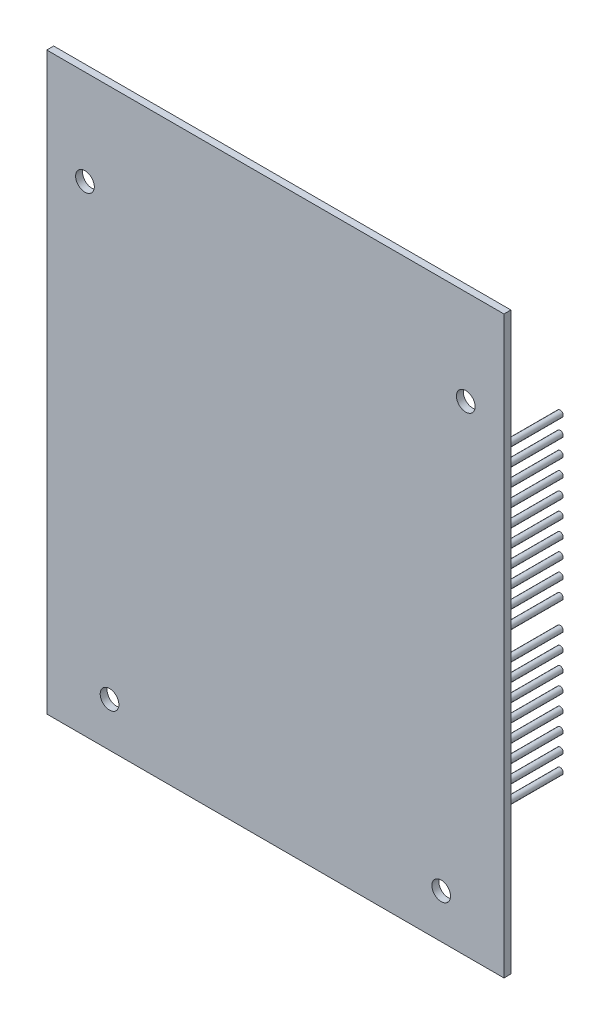
SolidWorks part; units mm, degrees
ref_plane "Alzado" through (0, 0, 0) normal (0, 0, 1) x (1, 0, 0)
ref_plane "Planta" through (0, 0, 0) normal (0, 1, 0) x (1, 0, 0)
ref_plane "Vista lateral" through (0, 0, 0) normal (1, 0, 0) x (0, 0, -1)
sketch "Croquis1" plane through (0, 0, 0) normal (0, 0, 1) x (1, 0, 0)
  line L1 (0, 83.058) -> (66.04, 83.058)
  line L2 (0, 83.058) -> (0, 0)
  line L3 (0, 0) -> (66.04, 0)
  line L4 (66.04, 83.058) -> (66.04, 0)
  dimension "D1" = 66.04
  dimension "D2" = 83.058
extrude "Saliente-Extruir1" add sketch "Croquis1" along normal blind 1
sketch "Croquis7" plane through (0, 0, 1) normal (0, 0, 1) x (1, 0, 0)
  line L0 (0, 6.3729) -> (66.04, 6.3729) construction
  line L1 (0, 83.058) -> (0, 0) construction
  line L2 (66.04, 0) -> (66.04, 83.058) construction
  line L3 (66.04, 69.375) -> (0, 69.375) construction
  line L4 (5.5194, 0) -> (5.5194, 83.058) construction
  line L5 (0, 0) -> (66.04, 0) construction
  line L6 (66.04, 83.058) -> (0, 83.058) construction
  line L7 (9.0678, 0) -> (9.0678, 83.058) construction
  line L8 (56.9722, 0) -> (56.9722, 83.058) construction
  line L9 (60.5206, 0) -> (60.5206, 83.058) construction
  line L10 (33.02, 83.058) -> (33.02, 0) construction
  dimension "D1" = 13.683
  dimension "D2" = 6.3729
  dimension "D3" = 9.0678
  dimension "D4" = 9.0678
  dimension "D5" = 5.5194
  dimension "D6" = 5.5194
  dimension "D7" = 23.9522
  dimension "D8" = 23.9522
  dimension "D9" = 27.5006
  dimension "D10" = 27.5006
hole_wizard "Taladro de margen para M2.51" positions "Croquis3D6" profile "Croquis8" hole size "M2.5" standard "ISO" end condition through all
sketch3d "Croquis3D6"
  line L0 (66.04, 69.375, 1) -> (0, 69.375, 1) construction
  line L1 (5.5194, 0, 1) -> (5.5194, 83.058, 1) construction
  line L2 (60.5206, 0, 1) -> (60.5206, 83.058, 1) construction
  line L3 (0, 6.3729, 1) -> (66.04, 6.3729, 1) construction
  line L4 (9.0678, 0, 1) -> (9.0678, 83.058, 1) construction
  line L5 (56.9722, 0, 1) -> (56.9722, 83.058, 1) construction
  point P0 (5.5194, 69.375, 1)
  point P6 (60.5206, 69.375, 1)
  point P10 (9.0678, 6.3729, 1)
  point P16 (56.9722, 6.3729, 1)
sketch "Croquis8" plane through (5.5194, 69.375, 1) normal (1, 0, 0) x (0, -1, 0)
  line L0 (0, 0) -> (0, 1)
  line L1 (0, 1) -> (1.35, 1)
  line L2 (1.35, 1) -> (1.35, 0)
  line L5 (1.35, 0) -> (0, 0)
  line L11 (0, -6.35) -> (0, 107.95) construction
  dimension "Diámetro de taladro hasta el siguiente" = 2.7
  dimension "Profundidad de taladro hasta el siguiente" = 1
sketch "Croquis9" plane through (0, 0, 1) normal (0, 0, 1) x (1, 0, 0)
  line L0 (0, 0) -> (66.04, 0) construction
  line L3 (0, 83.058) -> (0, 0) construction
  line L4 (66.04, 0) -> (66.04, 83.058) construction
  circle A0 centre (57.15, 57.658) radius 0.45
  circle A1 centre (57.15, 55.118) radius 0.45
  circle A2 centre (57.15, 52.578) radius 0.45
  circle A3 centre (57.15, 50.038) radius 0.45
  circle A4 centre (57.15, 44.958) radius 0.45
  circle A5 centre (57.15, 39.878) radius 0.45
  circle A6 centre (57.15, 37.338) radius 0.45
  circle A7 centre (57.15, 47.498) radius 0.45
  circle A8 centre (57.15, 42.418) radius 0.45
  circle A9 centre (57.15, 34.798) radius 0.45
  circle A10 centre (57.15, 30.734) radius 0.45
  circle A11 centre (57.15, 28.194) radius 0.45
  circle A12 centre (57.15, 25.654) radius 0.45
  circle A13 centre (57.15, 20.574) radius 0.45
  circle A14 centre (57.15, 23.114) radius 0.45
  circle A15 centre (57.15, 15.494) radius 0.45
  circle A16 centre (57.15, 18.034) radius 0.45
  circle A17 centre (8.89, 23.114) radius 0.45
  circle A18 centre (8.89, 20.574) radius 0.45
  circle A19 centre (8.89, 18.034) radius 0.45
  circle A20 centre (8.89, 15.494) radius 0.45
  circle A21 centre (8.89, 30.734) radius 0.45
  circle A22 centre (57.15, 12.954) radius 0.45
  circle A23 centre (8.89, 25.654) radius 0.45
  circle A24 centre (8.89, 12.954) radius 0.45
  circle A27 centre (8.89, 48.514) radius 0.45
  circle A28 centre (8.89, 45.974) radius 0.45
  circle A29 centre (8.89, 43.434) radius 0.45
  circle A30 centre (8.89, 38.354) radius 0.45
  circle A31 centre (8.89, 40.894) radius 0.45
  circle A32 centre (8.89, 33.274) radius 0.45
  circle A33 centre (8.89, 35.814) radius 0.45
  dimension "D1" = 0.9
  dimension "D14" = 2.54
  dimension "D20" = 0.9
  dimension "D2" = 2.54
  dimension "D3" = 2.54
  dimension "D4" = 2.54
  dimension "D5" = 2.54
  dimension "D6" = 2.54
  dimension "D7" = 2.54
  dimension "D8" = 2.54
  dimension "D9" = 2.54
  dimension "D10" = 4.064
  dimension "D11" = 2.54
  dimension "D12" = 2.54
  dimension "D13" = 2.54
  dimension "D15" = 2.54
  dimension "D16" = 2.54
  dimension "D17" = 2.54
  dimension "D18" = 12.954
  dimension "D19" = 2.54
  dimension "D21" = 2.54
  dimension "D22" = 2.54
  dimension "D23" = 2.54
  dimension "D24" = 2.54
  dimension "D25" = 5.08
  dimension "D26" = 2.54
  dimension "D27" = 2.54
  dimension "D28" = 12.954
  dimension "D29" = 8.89
  dimension "D30" = 2.54
  dimension "D31" = 2.54
  dimension "D32" = 2.54
  dimension "D33" = 2.54
  dimension "D34" = 2.54
  dimension "D35" = 2.54
  dimension "D36" = 8.89
extrude "Saliente-Extruir2" add sketch "Croquis9" against normal blind 17
